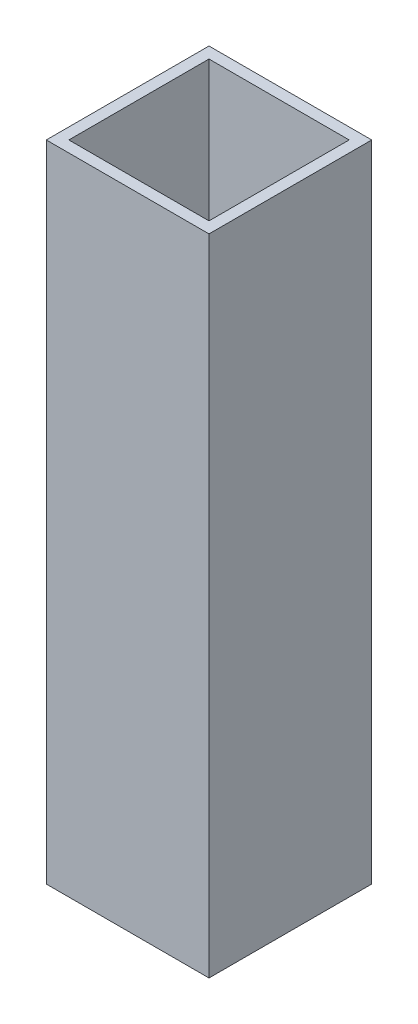
SolidWorks part; units mm, degrees
ref_plane "Front Plane" through (0, 0, 0) normal (0, 0, 1) x (1, 0, 0)
ref_plane "Top Plane" through (0, 0, 0) normal (0, 1, 0) x (1, 0, 0)
ref_plane "Right Plane" through (0, 0, 0) normal (1, 0, 0) x (0, 0, -1)
sketch "Sketch1" plane through (0, 0, 0) normal (0, 1, 0) x (1, 0, 0)
  line L1 (-11.049, -11.049) -> (11.049, -11.049)
  line L2 (-11.049, -11.049) -> (-11.049, 11.049)
  line L3 (-11.049, 11.049) -> (11.049, 11.049)
  line L4 (11.049, -11.049) -> (11.049, 11.049)
  line L5 (-11.049, -11.049) -> (11.049, 11.049) construction
  line L6 (-11.049, 11.049) -> (11.049, -11.049) construction
  line L7 (-12.827, -12.827) -> (12.827, -12.827)
  line L8 (-12.827, -12.827) -> (-12.827, 12.827)
  line L9 (-12.827, 12.827) -> (12.827, 12.827)
  line L10 (12.827, -12.827) -> (12.827, 12.827)
  line L11 (-12.827, -12.827) -> (12.827, 12.827) construction
  line L12 (-12.827, 12.827) -> (12.827, -12.827) construction
  point P0 (0, 0)
  point P6 (0, 0)
  dimension "D1" = 22.098
  dimension "D2" = 25.654
extrude "Boss-Extrude1" add sketch "Sketch1" along normal blind 101.6
